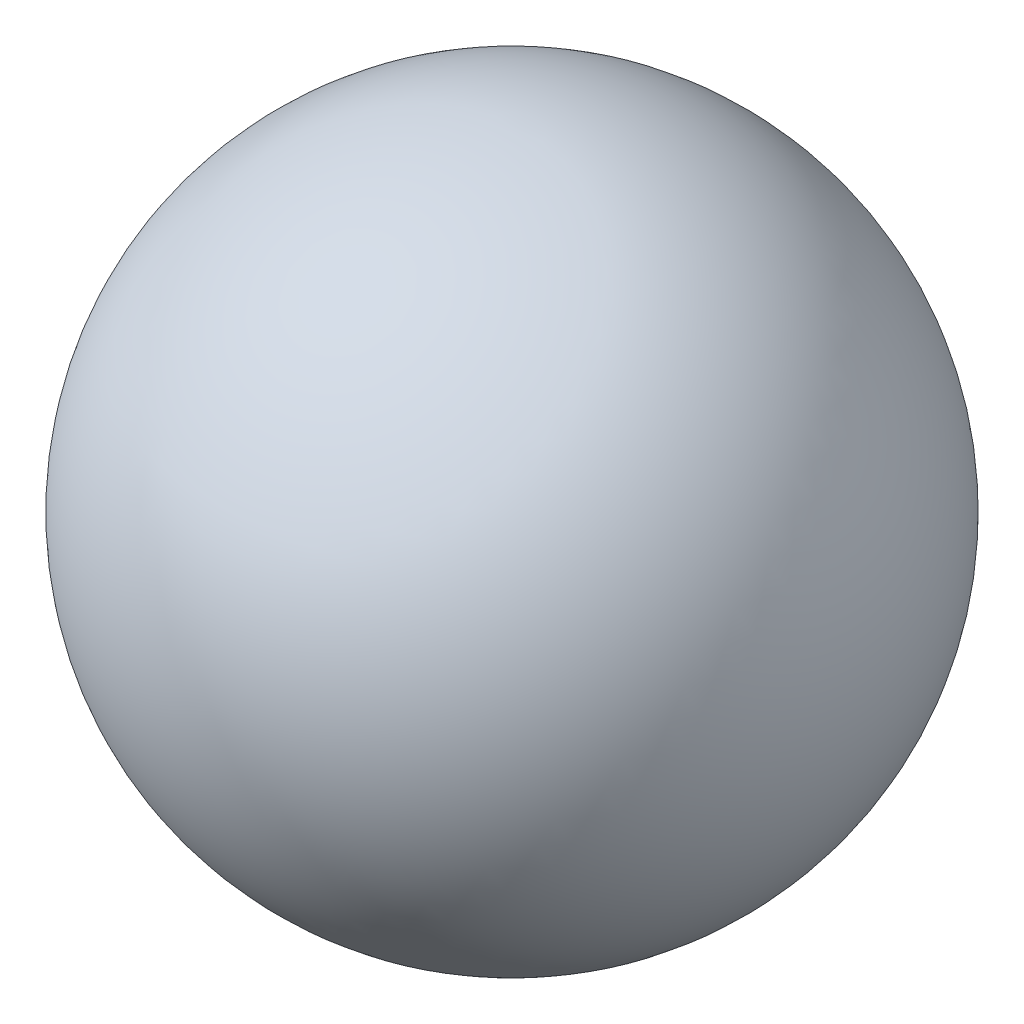
SolidWorks part; units mm, degrees
ref_plane "前基準面" through (0, 0, 0) normal (0, 0, 1) x (1, 0, 0)
ref_plane "上基準面" through (0, 0, 0) normal (0, 1, 0) x (1, 0, 0)
ref_plane "右基準面" through (0, 0, 0) normal (1, 0, 0) x (0, 0, -1)
sketch "草圖1" plane through (0, 0, 0) normal (1, 0, 0) x (0, 0, -1)
  line L0 (0, 10) -> (0, 0)
  line L1 (0, -120) -> (0, -130)
  line L2 (0, 69.7248) -> (0, -358.5076) construction
  arc A0 (0, 0) -> (0, -120) centre (0, -60) cw
  arc A1 (0, 10) -> (0, -130) centre (0, -60) cw
  dimension "D2" = 60
  dimension "D1" = 10
revolve "旋轉1" add sketch "草圖1" angle 360 about L2
